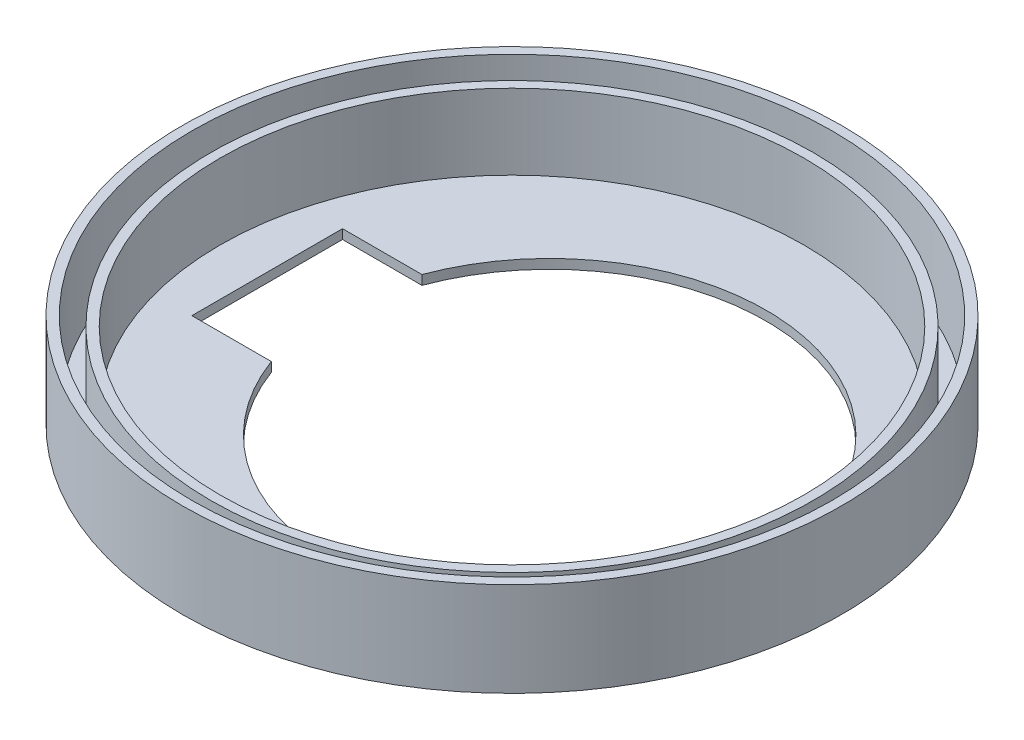
SolidWorks part; units mm, degrees
ref_plane "Front Plane" through (0, 0, 0) normal (0, 0, 1) x (1, 0, 0)
ref_plane "Top Plane" through (0, 0, 0) normal (0, 1, 0) x (1, 0, 0)
ref_plane "Right Plane" through (0, 0, 0) normal (1, 0, 0) x (0, 0, -1)
sketch "Sketch1" plane through (0, 0, 0) normal (0, 1, 0) x (1, 0, 0)
  circle A0 centre (0, 0) radius 17.5
extrude "Boss-Extrude1" add sketch "Sketch1" along normal blind 0.5
sketch "Sketch2" plane through (0, 0.5, 0) normal (0, 1, 0) x (1, 0, 0)
  circle A0 centre (2, 0) radius 11.5
extrude "Cut-Extrude1" cut sketch "Sketch2" against normal blind 0.5
sketch "Sketch3" plane through (0, 0, 0) normal (0, 1, 0) x (1, 0, 0)
  line L1 (2, 4) -> (-13, 4)
  line L2 (2, 4) -> (2, -4)
  line L3 (2, -4) -> (-13, -4)
  line L4 (-13, 4) -> (-13, -4)
extrude "Cut-Extrude4" cut sketch "Sketch3" along normal blind 2.5
sketch "Sketch4" plane through (0, 0, 0) normal (0, 1, 0) x (1, 0, 0)
  circle A0 centre (0, 0) radius 16
  circle A1 centre (0, 0) radius 15.5
extrude "Boss-Extrude2" add sketch "Sketch4" along normal blind 4.5
sketch "Sketch5" plane through (0, 0.5, 0) normal (0, 1, 0) x (1, 0, 0)
  circle A0 centre (0, 0) radius 14.5
  circle A1 centre (0, 0) radius 14.5
  circle A2 centre (0, 0) radius 14
sketch "Sketch6" plane through (0, 0.5, 0) normal (0, 1, 0) x (1, 0, 0)
  circle A0 centre (0, 0) radius 17.5
  circle A1 centre (0, 0) radius 17
extrude "Boss-Extrude4" add sketch "Sketch6" along normal blind 4.5
